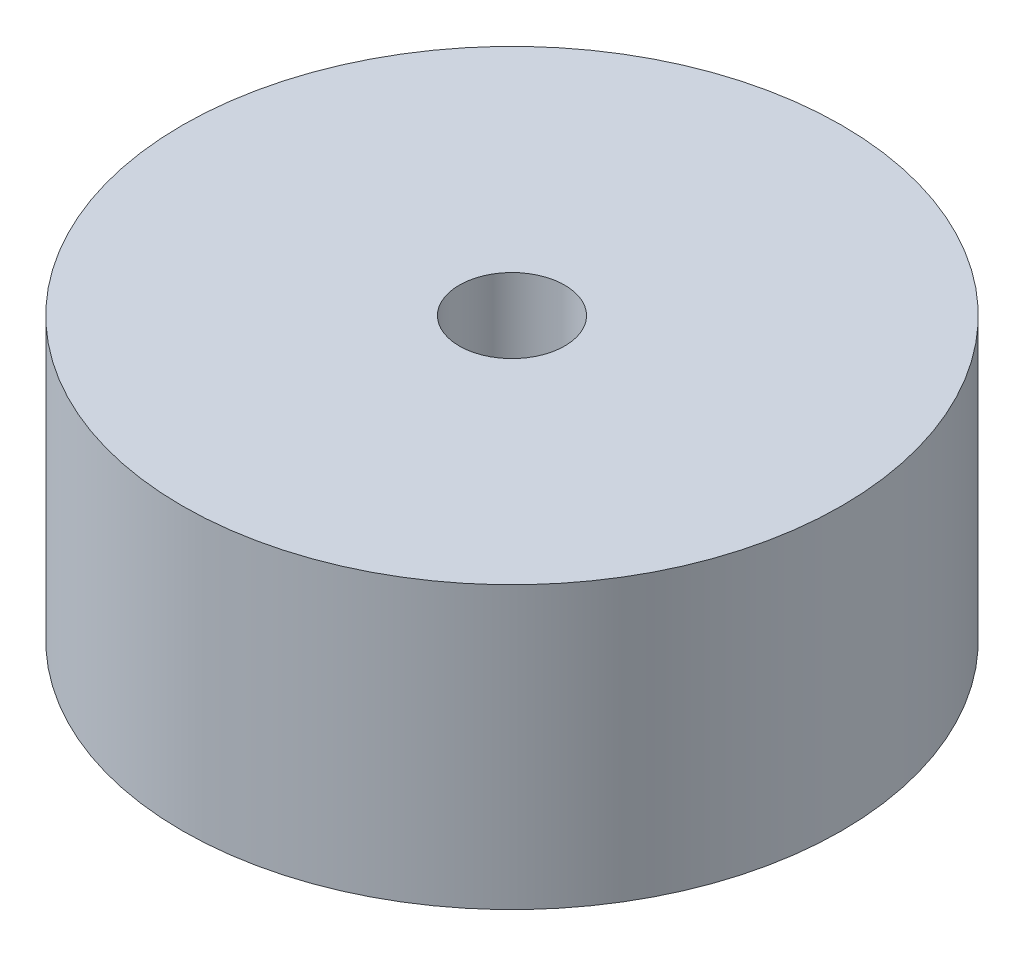
SolidWorks part; units mm, degrees
ref_plane "前视基准面" through (0, 0, 0) normal (0, 0, 1) x (1, 0, 0)
ref_plane "上视基准面" through (0, 0, 0) normal (0, 1, 0) x (1, 0, 0)
ref_plane "右视基准面" through (0, 0, 0) normal (1, 0, 0) x (0, 0, -1)
other "Configuration Table"
sketch "草图1" plane through (0, 0, 0) normal (0, 1, 0) x (1, 0, 0)
  circle A0 centre (0, 0) radius 37.5
  circle A1 centre (0, 0) radius 6
  dimension "D1" = 75
  dimension "D2" = 12
extrude "凸台-拉伸1" add sketch "草图1" along normal blind 32
